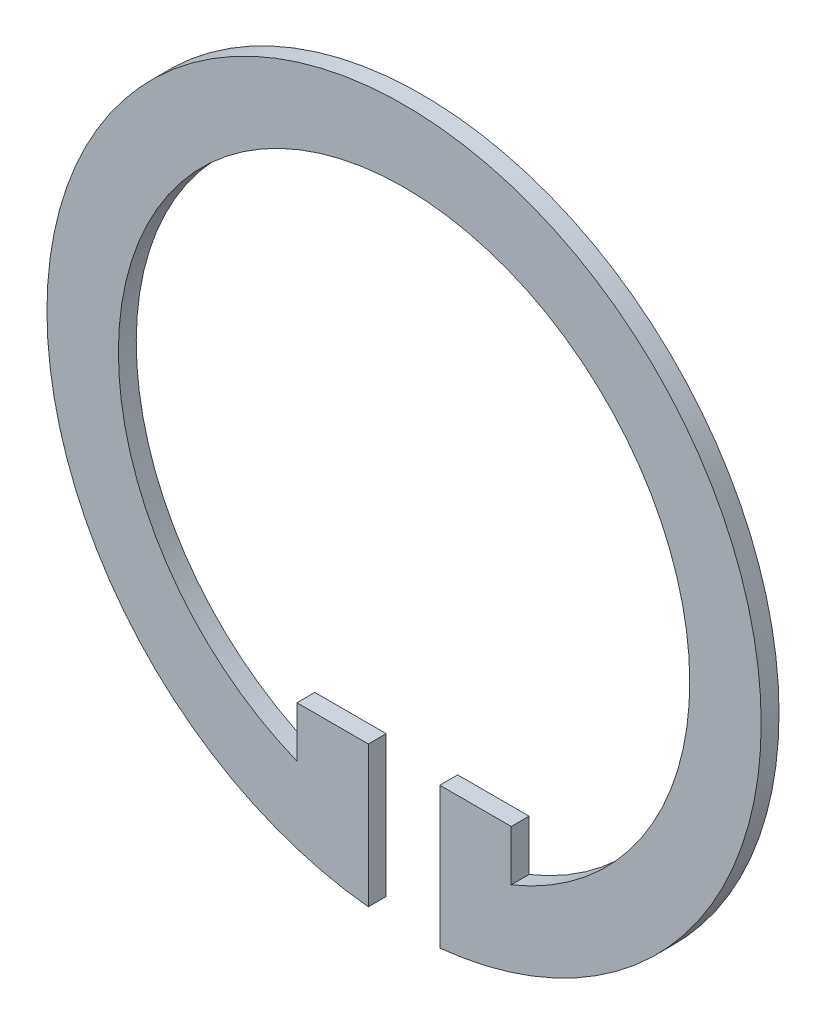
SolidWorks part; units mm, degrees
ref_plane "前视基准面" through (0, 0, 0) normal (0, 0, 1) x (1, 0, 0)
ref_plane "上视基准面" through (0, 0, 0) normal (0, 1, 0) x (1, 0, 0)
ref_plane "右视基准面" through (0, 0, 0) normal (1, 0, 0) x (0, 0, -1)
sketch "草图1" plane through (0, 0, 0) normal (0, 0, 1) x (1, 0, 0)
  line L0 (0, 18.0911) -> (0, -16.5006) construction
  line L1 (-1, -6) -> (-1, -9.9499)
  line L2 (1, -6) -> (1, -9.9499)
  line L3 (-3, -6) -> (-1, -6)
  line L4 (-3, -6) -> (-3, -7.4162)
  line L5 (3, -6) -> (3, -7.4162)
  line L7 (1, -6) -> (3, -6)
  arc A0 (1, -9.9499) -> (-1, -9.9499) centre (0, 0) ccw
  arc A1 (3, -7.4162) -> (-3, -7.4162) centre (0, 0) ccw
  dimension "D1" = 16
  dimension "D2" = 20
  dimension "D3" = 6
  dimension "D4" = 1
  dimension "D5" = 1
  dimension "D6" = 3
  dimension "D7" = 3
extrude "拉伸1" add sketch "草图1" along normal blind 0.5
